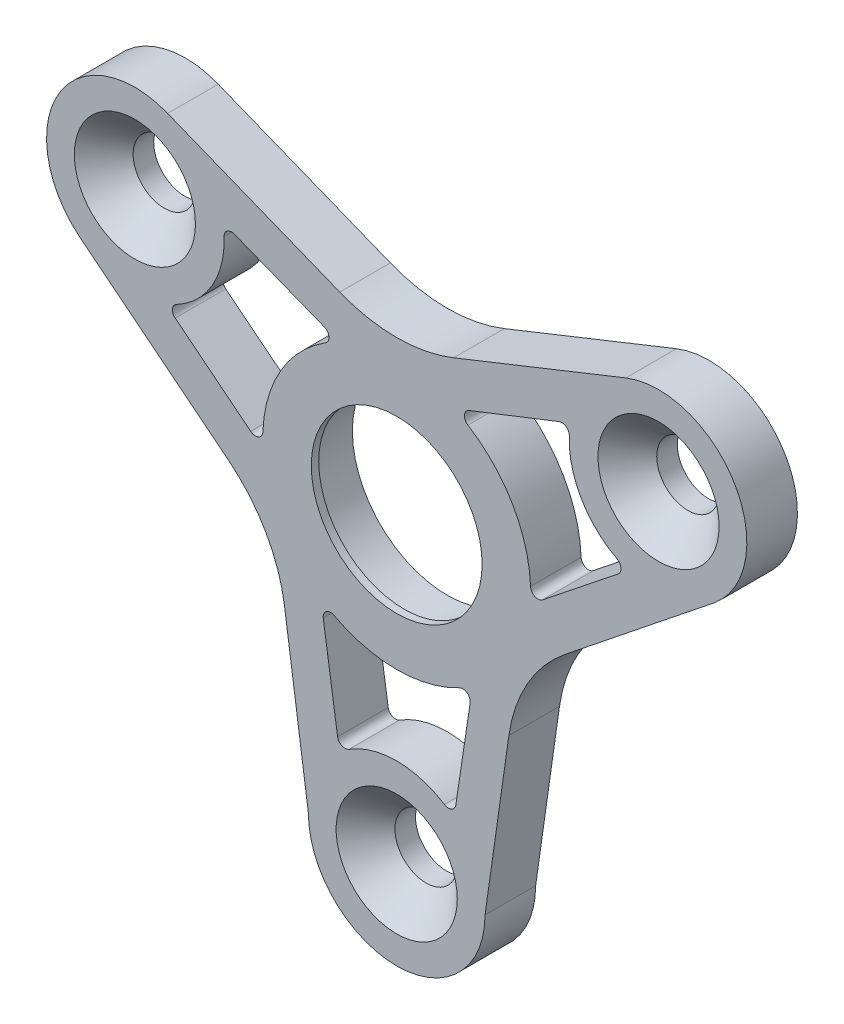
SolidWorks part; units mm, degrees
material "1060 合金"
ref_plane "前视基准面" through (0, 0, 0) normal (0, 0, 1) x (1, 0, 0)
ref_plane "上视基准面" through (0, 0, 0) normal (0, 1, 0) x (1, 0, 0)
ref_plane "右视基准面" through (0, 0, 0) normal (1, 0, 0) x (0, 0, -1)
sketch "草图1" plane through (0, 0, 0) normal (0, 0, 1) x (1, 0, 0)
  line L0 (-17.5933, 10.1575) -> (0, 0) construction
  line L1 (0, 0) -> (17.5933, 10.1575) construction
  line L2 (0, 0) -> (0, -20.315) construction
  line L3 (-15.3943, 15.6701) -> (-3.8237, 11.0545)
  line L4 (3.8237, 11.0545) -> (15.3943, 15.6701)
  line L5 (-21.2995, 5.522) -> (-11.3103, -2.4646)
  line L6 (-7.5381, -9.0688) -> (-5.935, -20.315)
  line L7 (21.2995, 5.522) -> (11.3103, -2.4646)
  line L8 (7.5381, -9.0688) -> (5.935, -20.315)
  circle A0 centre (0, 0) radius 5.74
  circle A1 centre (-17.5933, 10.1575) radius 2.095
  circle A2 centre (17.5933, 10.1575) radius 2.095
  circle A3 centre (0, -20.315) radius 2.095
  circle A4 centre (-17.5933, 10.1575) radius 5.935
  circle A5 centre (17.5933, 10.1575) radius 5.935
  circle A6 centre (0, -20.315) radius 5.935
  arc A7 (-3.8237, 11.0545) -> (3.8237, 11.0545) centre (0, 20.64) ccw
  arc A8 (-11.3103, -2.4646) -> (-7.5381, -9.0688) centre (-17.7548, -10.5251) cw
  arc A9 (11.3103, -2.4646) -> (7.5381, -9.0688) centre (17.7548, -10.5251) ccw
  dimension "D3" = 4.19
  dimension "D4" = 4.19
  dimension "D5" = 4.19
  dimension "D9" = 11.87
  dimension "D10" = 11.87
  dimension "D11" = 11.87
  dimension "D14" = 10.32
  dimension "D15" = 10.32
  dimension "D16" = 20.64
  dimension "D12" = 11.48
  dimension "D13" = 10.32
  dimension "D1" = 120
  dimension "D2" = 120
  dimension "D6" = 20.315
  dimension "D7" = 20.315
  dimension "D8" = 20.315
  dimension "D17" = 20.64
  dimension "D18" = 20.64
extrude "凸台-拉伸1" add sketch "草图1" along normal blind 3.4 contours A4 A1 | A5 A2 | A9 L7 A5 L4 A7 L3 A4 L5 A8 L6 A6 L8 A0 | A6 A3
sketch "草图2" plane through (0, 0, 3.4) normal (0, 0, 1) x (1, 0, 0)
  circle A0 centre (-17.5933, 10.1575) radius 4.07
  circle A1 centre (17.5933, 10.1575) radius 4.07
  circle A2 centre (0, -20.315) radius 4.07
  dimension "D1" = 8.14
  dimension "D2" = 8.14
  dimension "D3" = 8.14
sketch "草图3" plane through (0, 0, 0) normal (0, 0, -1) x (-1, 0, 0)
  circle A0 centre (0, 0) radius 6.38
  dimension "D1" = 12.76
extrude "切除-拉伸1" cut sketch "草图3" against normal blind 2.9
sketch "草图4" plane through (0, 0, 0) normal (0, 0, -1) x (-1, 0, 0)
  circle A0 centre (0, -20.315) radius 4.5
  circle A1 centre (17.5933, 10.1575) radius 4.5
  circle A2 centre (-17.5933, 10.1575) radius 4.5
  dimension "D1" = 9
  dimension "D2" = 9
  dimension "D3" = 9
extrude "凸台-拉伸3" add sketch "草图4" along normal blind 0.56
sketch "草图6" plane through (0, 0, -0.56) normal (0, 0, -1) x (-1, 0, 0)
  circle A0 centre (0, -20.315) radius 3.15
  dimension "D1" = 6.3
extrude "切除-拉伸2" cut sketch "草图6" against normal blind 0.6
sketch "草图7" plane through (0, 0, -0.56) normal (0, 0, -1) x (-1, 0, 0)
  circle A0 centre (-17.5933, 10.1575) radius 3.15
  dimension "D1" = 6.3
extrude "切除-拉伸3" cut sketch "草图7" against normal blind 0.6
sketch "草图8" plane through (0, 0, -0.56) normal (0, 0, -1) x (-1, 0, 0)
  circle A0 centre (17.5933, 10.1575) radius 3.15
  dimension "D1" = 6.3
extrude "切除-拉伸4" cut sketch "草图8" against normal blind 0.6
ref_plane "基准面1" through (0, 10.1575, 0) normal (0, -1, 0) x (-1, 0, 0)
sketch "草图9" plane through (0, 10.1575, 0) normal (0, -1, 0) x (-1, 0, 0)
  line L0 (15.4983, -3.4) -> (15.4983, 9.3358) construction
  line L1 (19.6883, -3.4) -> (19.6883, 9.3358) construction
  line L3 (19.6883, -3.4) -> (19.6883, -1.425)
  line L4 (19.6883, -1.425) -> (21.6633, -3.4)
  line L5 (21.6633, -3.4) -> (19.6883, -3.4)
  line L7 (17.5933, -3.4) -> (17.5933, 5.8602) construction
  dimension "D1" = 1.975
  dimension "D2" = 45
revolve "切除-旋转1" cut sketch "草图9" angle 360 about L7
ref_plane "基准面2" through (8.7967, -5.0787, 0) normal (-0.866, 0.5, 0) x (0, 0, 1)
sketch "草图10" plane through (8.7967, -5.0787, 0) normal (-0.866, 0.5, 0) x (0, 0, 1)
  line L0 (3.4, 19.6883) -> (3.4, 21.6633)
  line L1 (3.4, 21.6633) -> (1.425, 19.6883)
  line L2 (1.425, 19.6883) -> (3.4, 19.6883)
  line L5 (3.4, 17.5933) -> (0, 17.5933) construction
  dimension "D1" = 45
revolve "切除-旋转2" cut sketch "草图10" angle 360 about L5
sketch "草图11" plane through (8.7967, -5.0787, 0) normal (-0.866, 0.5, 0) x (0, 0, 1)
  line L0 (3.4, -15.4983) -> (3.4, -13.5233)
  line L1 (3.4, -13.5233) -> (1.425, -15.4983)
  line L2 (1.425, -15.4983) -> (3.4, -15.4983)
  line L7 (3.4, -17.5933) -> (0, -17.5933) construction
  dimension "D1" = 45
revolve "切除-旋转3" cut sketch "草图11" angle 360 about L7
sketch "草图12" plane through (0, 0, 0) normal (0, 0, -1) x (-1, 0, 0)
  line L0 (3.9712, -14.8973) -> (4.9366, -8.4717)
  line L1 (-3.9712, -14.8973) -> (-4.9366, -8.4717)
  line L2 (-10.9158, 10.8878) -> (-4.8685, 8.5111)
  line L3 (-14.887, 4.0095) -> (-9.805, -0.0393)
  line L4 (14.887, 4.0095) -> (9.805, -0.0393)
  line L5 (10.9158, 10.8878) -> (4.8685, 8.5111)
  circle A1 centre (17.5933, 10.1575) radius 6
  circle A2 centre (-17.5933, 10.1575) radius 6
  arc A4 (3.2093, -15.2454) -> (-3.2093, -15.2454) centre (0, -20.315) ccw
  arc A5 (4.2084, -7.9555) -> (-4.2084, -7.9555) centre (0, 0) cw
  arc A6 (-4.2084, -7.9555) -> (-4.9366, -8.4717) centre (-4.4421, -8.3975) ccw
  arc A7 (-3.9712, -14.8973) -> (-3.2093, -15.2454) centre (-3.4767, -14.823) ccw
  arc A8 (3.9712, -14.8973) -> (3.2093, -15.2454) centre (3.4767, -14.823) cw
  arc A9 (4.9366, -8.4717) -> (4.2084, -7.9555) centre (4.4421, -8.3975) ccw
  arc A10 (-8.9938, 0.3332) -> (-4.7855, 7.6223) centre (0, 0) cw
  arc A11 (-9.805, -0.0393) -> (-8.9938, 0.3332) centre (-9.4935, 0.3517) ccw
  arc A12 (-4.7855, 7.6223) -> (-4.8685, 8.5111) centre (-5.0513, 8.0457) ccw
  arc A13 (-10.9158, 10.8878) -> (-11.5983, 10.402) centre (-11.0987, 10.4224) ccw
  arc A14 (-14.8076, 4.8434) -> (-11.5983, 10.402) centre (-17.5933, 10.1575) ccw
  arc A15 (-14.887, 4.0095) -> (-14.8076, 4.8434) centre (-14.5754, 4.4006) cw
  arc A16 (4.7855, 7.6223) -> (8.9938, 0.3332) centre (0, 0) cw
  arc A17 (4.8685, 8.5111) -> (4.7855, 7.6223) centre (5.0513, 8.0457) ccw
  arc A18 (8.9938, 0.3332) -> (9.805, -0.0393) centre (9.4935, 0.3517) ccw
  arc A19 (14.887, 4.0095) -> (14.8076, 4.8434) centre (14.5754, 4.4006) ccw
  arc A20 (11.5983, 10.402) -> (14.8076, 4.8434) centre (17.5933, 10.1575) ccw
  arc A21 (10.9158, 10.8878) -> (11.5983, 10.402) centre (11.0987, 10.4224) cw
  point P51 (0, 0)
  dimension "D1" = 0.5
  dimension "D2" = 12
  dimension "D3" = 12
  dimension "D4" = 3
  dimension "D7" = 6
  dimension "D8" = 9
  dimension "D9" = 17.089
  dimension "D5" = 6.4976
  dimension "D6" = 6.4976
extrude "切除-拉伸5" cut sketch "草图12" against normal blind 10 contours A21 L5 A17 A16 A18 L4 A19 A1 | L0 A9 A5 A6 L1 A7 A4 A8 | A15 L3 A11 A10 A12 L2 A13 A2
sketch "草图13" plane through (0, 0, -0.56) normal (0, 0, -1) x (-1, 0, 0)
  circle A1 centre (0, -20.315) radius 4.5
  circle A2 centre (0, -20.315) radius 4.5
  circle M2 centre (0, -20.315) radius 3.15
  circle M3 centre (0, -20.315) radius 4.5
  dimension "D1" = 0
extrude "切除-拉伸6" cut sketch "草图13" against normal blind 0.37 contours M3 M2
sketch "草图14" plane through (0, 0, -0.56) normal (0, 0, -1) x (-1, 0, 0)
  circle A1 centre (-17.5933, 10.1575) radius 4.5
  circle A2 centre (-17.5933, 10.1575) radius 4.5
  circle M2 centre (-17.5933, 10.1575) radius 3.15
  circle M3 centre (-17.5933, 10.1575) radius 4.5
  dimension "D1" = 0
extrude "切除-拉伸7" cut sketch "草图14" against normal blind 0.37 contours M3 M2
sketch "草图15" plane through (0, 0, -0.56) normal (0, 0, -1) x (-1, 0, 0)
  circle A1 centre (17.5933, 10.1575) radius 4.5
  circle A2 centre (17.5933, 10.1575) radius 4.5
  circle M2 centre (17.5933, 10.1575) radius 3.15
  circle M3 centre (17.5933, 10.1575) radius 4.5
  dimension "D1" = 0
extrude "切除-拉伸8" cut sketch "草图15" against normal blind 0.37 contours M3 M2
